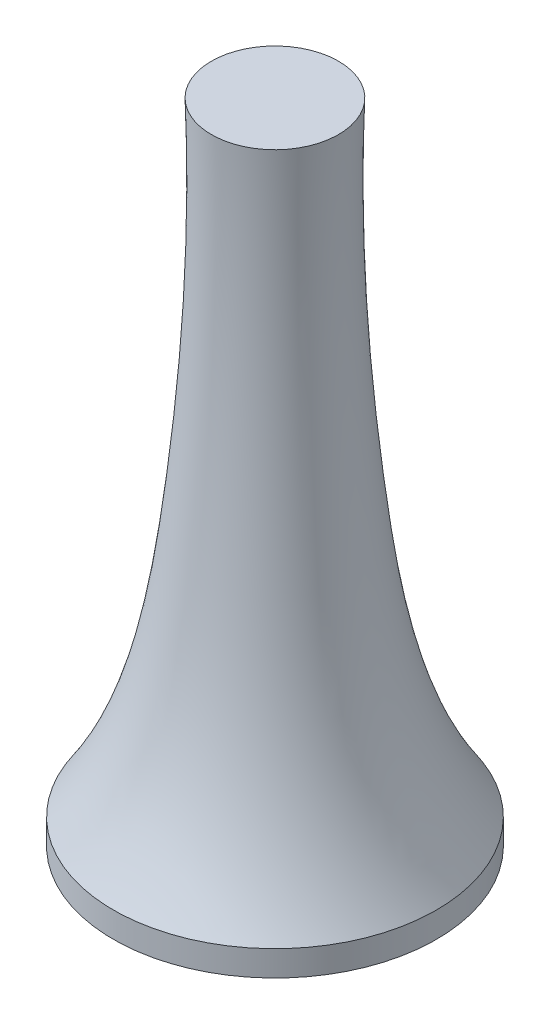
SolidWorks part; units mm, degrees
ref_plane "Front Plane" through (0, 0, 0) normal (0, 0, 1) x (1, 0, 0)
ref_plane "Top Plane" through (0, 0, 0) normal (0, 1, 0) x (1, 0, 0)
ref_plane "Right Plane" through (0, 0, 0) normal (1, 0, 0) x (0, 0, -1)
sketch "Sketch1" plane through (0, 0, 0) normal (0, 0, 1) x (1, 0, 0)
  line L0 (2.54, 0.4) -> (2.54, 0)
  line L1 (0, 0) -> (2.54, 0)
  line L2 (0, 0) -> (0, 10.192)
  line L3 (0, 10.192) -> (1, 10.192)
  spline S0 degree 3 poles (1, 10.192) (0.9363, 8.3387) (1.1074, 5.0143) (1.6814, 1.6727) (2.54, 0.4) knots 0 0 0 0 0.552959 1 1 1 1
  point P1 (1.6968, 4.7995)
  point P7 (2.7828, 2.5562)
  point P8 (1.5188, 4.5858)
  point P10 (0, 0)
  point P12 (2.0799, 2.4512)
  point P14 (1, 7.1984)
  point P15 (1.2487, 4.6569)
  point P16 (1.7261, 2.1426)
  point P17 (1, 7.8896)
  dimension "D1" = 10.192
  dimension "D2" = 1
  dimension "D3" = 0.4
  dimension "D4" = 2.54
revolve "Revolve1" add sketch "Sketch1" angle 360 about L2
